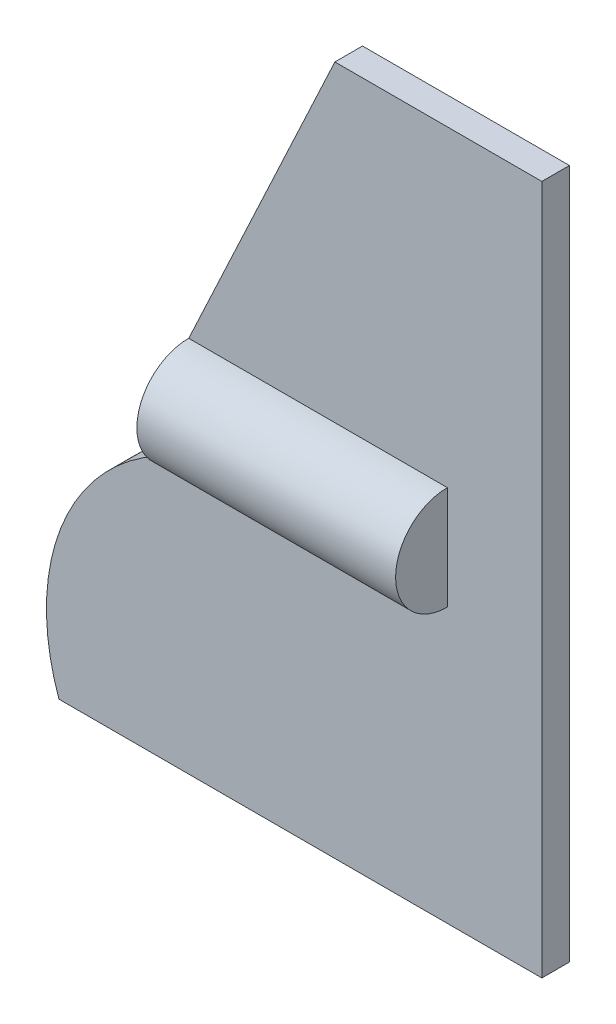
SolidWorks part; units mm, degrees
material "ABS"
ref_plane "Front Plane" through (0, 0, 0) normal (0, 0, 1) x (1, 0, 0)
ref_plane "Top Plane" through (0, 0, 0) normal (0, 1, 0) x (1, 0, 0)
ref_plane "Right Plane" through (0, 0, 0) normal (1, 0, 0) x (0, 0, -1)
sketch "Sketch1" plane through (0, 0, 0) normal (0, 0, 1) x (1, 0, 0)
  line L0 (0, 0) -> (70, 0)
  line L1 (70, 0) -> (70, 100)
  line L2 (70, 100) -> (40, 100)
  line L3 (40, 100) -> (18.8128, 54.7109)
  line L4 (18.8128, 54.7109) -> (18.8128, 39.7109)
  arc A3 (18.8128, 39.7109) -> (0, 0) centre (29.2618, 10.4491) ccw
  dimension "D1" = 70
  dimension "D2" = 100
  dimension "D3" = 30
  dimension "D4" = 50
  dimension "D5" = 15
extrude "Boss-Extrude1" add sketch "Sketch1" along normal blind 4
ref_plane "Plane1" through (18.8, 0, 0) normal (1, 0, 0) x (0, 0, -1)
sketch "Sketch5" plane through (18.8, 0, 0) normal (1, 0, 0) x (0, 0, -1)
  line L0 (-4, 54.7109) -> (-4, 39.7109)
  arc A0 (-4, 54.7109) -> (-4, 39.7109) centre (-4, 47.2109) ccw
extrude "Boss-Extrude2" add sketch "Sketch5" along normal blind 37.5
sketch "Sketch7" plane through (18.8, 0, 0) normal (1, 0, 0) x (0, 0, -1)
  circle A0 centre (-5.6906, 47.2109) radius 5
  dimension "D1" = 10
extrude "Cut-Extrude1" cut sketch "Sketch7" along normal blind 30
mirror "Mirror1" [suppressed]
delete or keep bodies "Body-Delete/Keep 1" [suppressed] type delete bodies bodies 103
sketch "Sketch8" [suppressed] plane through (0, 0, 0) normal (0, 0, 1) x (1, 0, 0)
  line L0 (64.7835, 100) -> (70, 100)
  line L1 (70, 100) -> (40, 100) construction
  line L2 (70, 100) -> (70, 0)
  line L3 (70, 0) -> (64.7835, 0)
  line L4 (0, 0) -> (70, 0) construction
  line L5 (64.7835, 0) -> (64.7835, 100)
extrude "Cut-Extrude3" [suppressed] cut sketch "Sketch8" against normal through all
